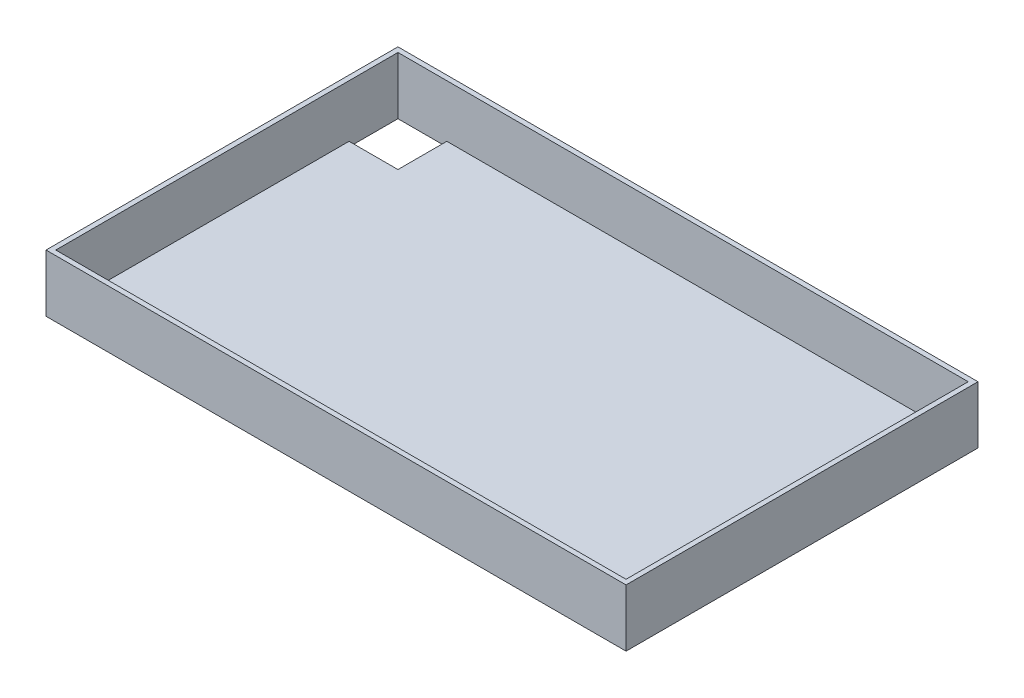
SolidWorks part; units mm, degrees
ref_plane "Front Plane" through (0, 0, 0) normal (0, 0, 1) x (1, 0, 0)
ref_plane "Top Plane" through (0, 0, 0) normal (0, 1, 0) x (1, 0, 0)
ref_plane "Right Plane" through (0, 0, 0) normal (1, 0, 0) x (0, 0, -1)
sketch "Sketch1" plane through (0, 0, 0) normal (0, 1, 0) x (1, 0, 0)
  line L1 (-175, 105) -> (175, 105)
  line L2 (-175, 105) -> (-175, -105)
  line L3 (-175, -105) -> (175, -105)
  line L4 (175, 105) -> (175, -105)
  line L5 (-175, 105) -> (175, -105) construction
  line L6 (-175, -105) -> (175, 105) construction
  point P0 (0, 0)
  dimension "D1" = 350
  dimension "D2" = 210
extrude "Boss-Extrude1" add sketch "Sketch1" along normal blind 32.22
shell "Shell1" thickness 3
sketch "Sketch2" plane through (0, 0, 0) normal (0, 1, 0) x (1, 0, 0)
  line L1 (175, 105) -> (145, 105)
  line L2 (175, 105) -> (175, 75)
  line L3 (175, 75) -> (145, 75)
  line L4 (145, 105) -> (145, 75)
  dimension "D1" = 30
  dimension "D2" = 30
extrude "Cut-Extrude2" cut sketch "Sketch2" against normal through all
mirror "Mirror1" about plane through (0, 0, 0) normal (0, 0, 1) of "Cut-Extrude2"
mirror "Mirror2" about plane through (0, 0, 0) normal (1, 0, 0) of "Mirror1", "Cut-Extrude2"
